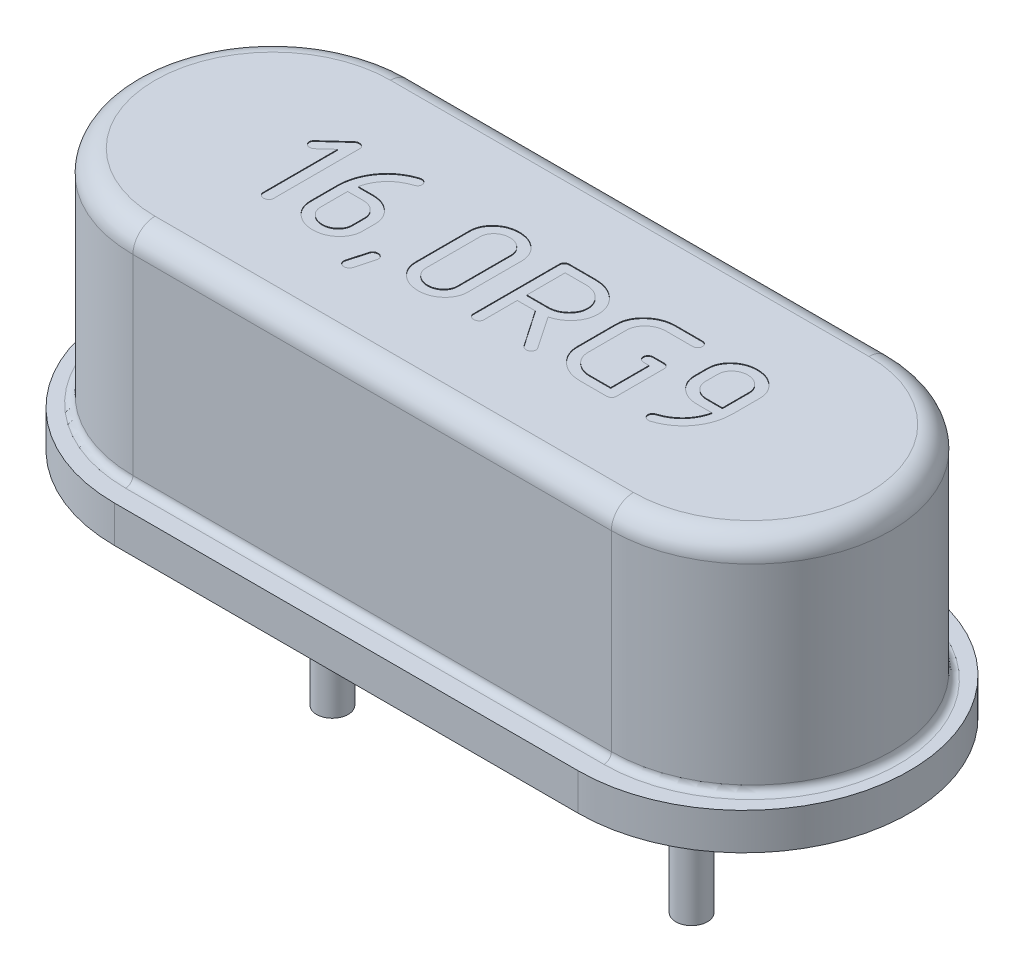
SolidWorks part; units mm, degrees
ref_plane "Спереди" through (0, 0, 0) normal (0, 0, 1) x (1, 0, 0)
ref_plane "Сверху" through (0, 0, 0) normal (0, 1, 0) x (1, 0, 0)
ref_plane "Справа" through (0, 0, 0) normal (1, 0, 0) x (0, 0, -1)
sketch "Эскиз1" plane through (0, 0, 0) normal (0, 1, 0) x (1, 0, 0)
  line L0 (3.15, 0) -> (-3.15, 0) construction
  line L1 (3.15, -2.25) -> (-3.15, -2.25)
  line L2 (3.15, 2.25) -> (-3.15, 2.25)
  arc A0 (3.15, -2.25) -> (3.15, 2.25) centre (3.15, 0) ccw
  arc A1 (-3.15, 2.25) -> (-3.15, -2.25) centre (-3.15, 0) ccw
  point P2 (0, 0)
  dimension "D1" = 2.25
  dimension "D2" = 3.15
extrude "Boss-Extrude1" add sketch "Эскиз1" along normal blind 0.5 from offset 0.05
sketch "Эскиз2" plane through (0, 0.55, 0) normal (0, 1, 0) x (1, 0, 0)
  line L0 (3.25, 0) -> (-3.25, 0) construction
  line L1 (3.25, -1.9) -> (-3.25, -1.9)
  line L2 (3.25, 1.9) -> (-3.25, 1.9)
  arc A0 (3.25, -1.9) -> (3.25, 1.9) centre (3.25, 0) ccw
  arc A1 (-3.25, 1.9) -> (-3.25, -1.9) centre (-3.25, 0) ccw
  point P2 (0, 0)
  dimension "D2" = 1.9
  dimension "D1" = 3.25
extrude "Boss-Extrude2" add sketch "Эскиз2" along normal blind 3
sketch "Эскиз3" plane through (0, 0.05, 0) normal (0, -1, 0) x (1, 0, 0)
  line L0 (0, 0) -> (6.0233, 0) construction
  line L1 (0, -1000) -> (0, 49000) construction
  circle A0 centre (2.44, 0) radius 0.645
  circle A1 centre (-2.44, 0) radius 0.645
  point P1 (0, 0)
  dimension "D1" = 1.29
  dimension "D2" = 4.88
extrude "Cut-Extrude1" cut sketch "Эскиз3" against normal blind 0.1
sketch "Эскиз4" plane through (0, 0.15, 0) normal (0, -1, 0) x (1, 0, 0)
  line L0 (0, -1000) -> (0, 49000) construction
  circle A0 centre (2.44, 0) radius 0.215
  circle A1 centre (2.44, 0) radius 0.645 construction
  circle A2 centre (-2.44, 0) radius 0.215
  dimension "D1" = 0.43
extrude "Boss-Extrude3" add sketch "Эскиз4" along normal offset from surface (2.75 mm away) 2.6 separate body up to plane "Сверху" offset beyond the face yes
sketch "Эскиз6" plane through (0, 3.55, 0) normal (0, 1, 0) x (1, 0, 0)
  line L0 (-4, -0.65) -> (4, -0.65) construction
  line L4 (0, 0) -> (0, -3.0022) construction
  text T0 "16,0RG9" font "OpenGost Type B TT" height 1.3
  point P10 (2.2262, 0.4268)
  dimension "D3" = 4
  dimension "D4" = 4
  dimension "D1" = 0.65
extrude "Cut-Extrude2" cut sketch "Эскиз6" against normal blind 0.01
fillet "Fillet1" radius 0.1 4 edges at (0, 0.55, -1.9) (5.15, 0.55, 0) (0, 0.55, 1.9) (-5.15, 0.55, 0)
fillet "Fillet2" radius 0.3 4 edges at (-5.15, 3.55, 0) (0, 3.55, -1.9) (5.15, 3.55, 0) (0, 3.55, 1.9)
equation "\"D4@Эскиз6\"=\"D3@Эскиз6\""
